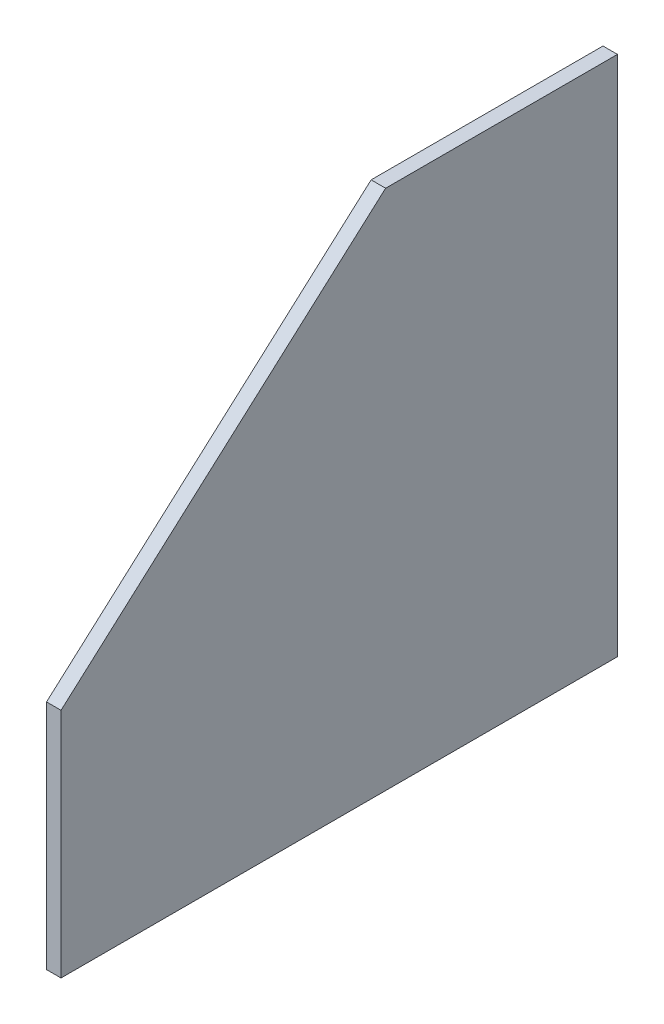
SolidWorks part; units mm, degrees
material "6061-T6 (SS)"
ref_plane "Front Plane" through (0, 0, 0) normal (0, 0, 1) x (1, 0, 0)
ref_plane "Top Plane" through (0, 0, 0) normal (0, 1, 0) x (1, 0, 0)
ref_plane "Right Plane" through (0, 0, 0) normal (1, 0, 0) x (0, 0, -1)
sketch "Sketch1" plane through (0, 0, 0) normal (1, 0, 0) x (0, 0, -1)
  line L0 (0, 0) -> (0, 114.3)
  line L1 (0, 114.3) -> (-50.8, 114.3)
  line L2 (-50.8, 114.3) -> (-121.92, 50.8)
  line L3 (-121.92, 50.8) -> (-121.92, 0)
  line L4 (-121.92, 0) -> (0, 0)
  dimension "D1" = 50.8
  dimension "D2" = 114.3
  dimension "D3" = 121.92
extrude "Boss-Extrude1" add sketch "Sketch1" along normal blind 3.175
